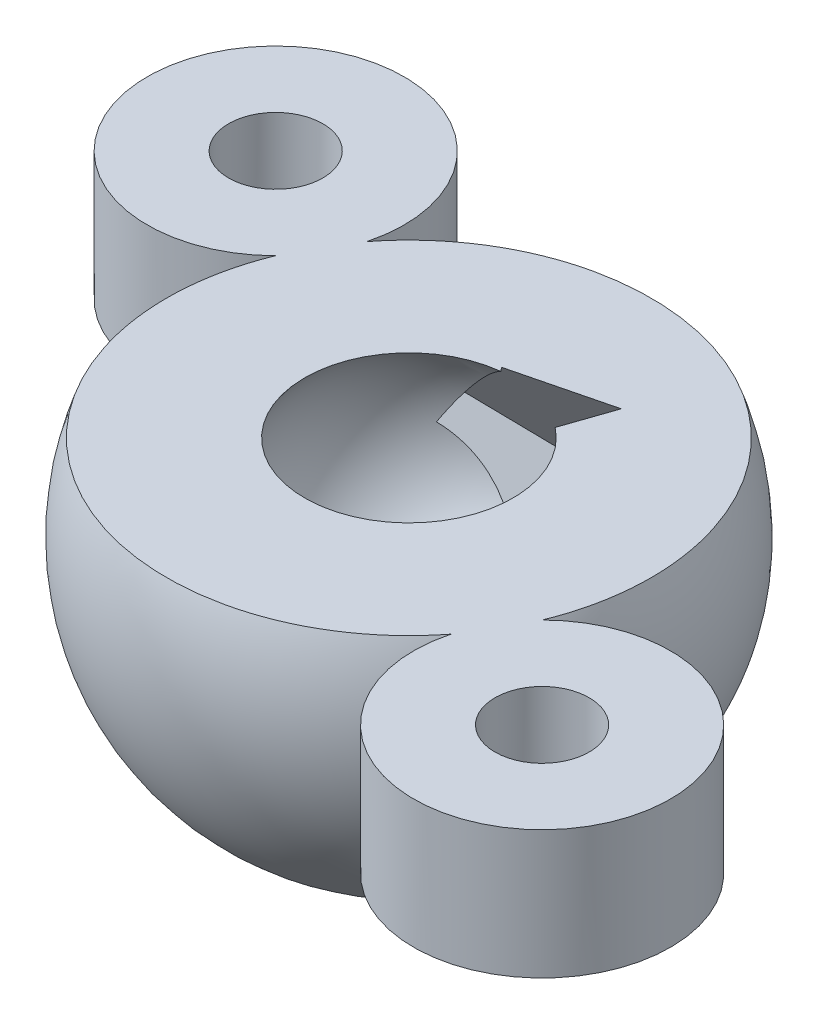
SolidWorks part; units mm, degrees
other "Compression Link 2 Fixed Ball Retainer"
ref_plane "Front Plane" through (0, 0, 0) normal (0, 0, 1) x (1, 0, 0)
ref_plane "Top Plane" through (0, 0, 0) normal (0, 1, 0) x (1, 0, 0)
ref_plane "Right Plane" through (0, 0, 0) normal (1, 0, 0) x (0, 0, -1)
sketch3d "Retainer Dome axis line"
  line L0 (-62.6314, -73, 30.9808) -> (-79.9519, -73, 20.9808) construction
ref_axis "Retainer Dome axis" through (-62.6314, -73, 30.9808) along (-0.866, 0, -0.5)
sketch3d "Retainer Dome Sketch datum points"
  point P0 (-71.2917, -73, 25.9808)
  point P1 (-76.2917, -73, 34.641)
  point P2 (-79.9519, -73, 20.9808)
ref_plane "Retainer Dome Sketch plane" through (0, -73, 0) normal (0, -1, 0) x (-1, 0, 0)
sketch "Retainer Dome Sketch" plane through (0, -73, 0) normal (0, -1, 0) x (-1, 0, 0)
  line L0 (76.4878, -22.9808) -> (66.0955, -28.9808)
  arc A0 (66.0955, -28.9808) -> (76.4878, -22.9808) centre (71.2917, -25.9808) ccw
revolve "Retainer Dome" add sketch "Retainer Dome Sketch" angle 360 about axis through (-62.6314, -73, 30.9808) along (-0.866, 0, -0.5)
sketch3d "Dome Trim Sketch datum points"
  point P0 (-61.7295, -71, 23.4186)
  point P1 (-66.7295, -71, 32.0788)
  point P2 (-61.7295, -61, 23.4186)
ref_plane "Dome Trim Sketch plane" through (-36.1566, 0, -20.875) normal (-0.866, 0, -0.5) x (-0.5, 0, 0.866)
sketch "Dome Trim Sketch" plane through (-36.1566, 0, -20.875) normal (-0.866, 0, -0.5) x (-0.5, 0, 0.866)
  line L0 (51.1458, -71) -> (65.1458, -71)
  line L1 (65.1458, -71) -> (65.1458, -66)
  line L2 (65.1458, -66) -> (51.1458, -66)
  line L3 (51.1458, -66) -> (51.1458, -71)
extrude "Dome Trim" cut sketch "Dome Trim Sketch" along normal blind 14
sketch3d "Retainer Feature 3 profile datum points"
  point P0 (-63.9304, -71, 30.2308)
  point P1 (-53.9304, -71, 30.2308)
  point P2 (-63.9304, -71, 40.2308)
ref_plane "Retainer Feature 3 profile plane" through (0, -71, 0) normal (0, -1, 0) x (-1, 0, 0)
sketch "Retainer Feature 3 profile" plane through (0, -71, 0) normal (0, -1, 0) x (-1, 0, 0)
  circle A0 centre (63.9304, -30.2308) radius 3
extrude "Retainer Feature 3" add sketch "Retainer Feature 3 profile" along normal blind 3
sketch3d "Retainer Feature 4 profile datum points"
  point P0 (-78.6529, -71, 21.7308)
  point P1 (-68.6529, -71, 21.7308)
  point P2 (-78.6529, -71, 31.7308)
ref_plane "Retainer Feature 4 profile plane" through (0, -71, 0) normal (0, -1, 0) x (-1, 0, 0)
sketch "Retainer Feature 4 profile" plane through (0, -71, 0) normal (0, -1, 0) x (-1, 0, 0)
  circle A0 centre (78.6529, -21.7308) radius 3
extrude "Retainer Feature 4" add sketch "Retainer Feature 4 profile" along normal blind 3
sketch3d "Spherical Seat axis line"
  line L0 (-62.6314, -73, 30.9808) -> (-79.9519, -73, 20.9808) construction
ref_axis "Spherical Seat axis" through (-62.6314, -73, 30.9808) along (-0.866, 0, -0.5)
sketch3d "Spherical Seat Sketch datum points"
  point P0 (-71.2917, -73, 25.9808)
  point P1 (-76.2917, -73, 34.641)
  point P2 (-79.9519, -73, 20.9808)
ref_plane "Spherical Seat Sketch plane" through (0, -73, 0) normal (0, -1, 0) x (-1, 0, 0)
sketch "Spherical Seat Sketch" plane through (0, -73, 0) normal (0, -1, 0) x (-1, 0, 0)
  line L0 (74.0196, -24.4058) -> (68.5637, -27.5558)
  arc A0 (68.5637, -27.5558) -> (74.0196, -24.4058) centre (71.2917, -25.9808) ccw
revolve "Spherical Seat" cut sketch "Spherical Seat Sketch" angle 360 about axis through (-62.6314, -73, 30.9808) along (-0.866, 0, -0.5)
sketch3d "Retainer Feature 6 profile datum points"
  point P0 (-63.9304, -70, 30.2308)
  point P1 (-53.9304, -70, 30.2308)
  point P2 (-63.9304, -70, 40.2308)
ref_plane "Retainer Feature 6 profile plane" through (0, -70, 0) normal (0, -1, 0) x (-1, 0, 0)
sketch "Retainer Feature 6 profile" plane through (0, -70, 0) normal (0, -1, 0) x (-1, 0, 0)
  circle A0 centre (63.9304, -30.2308) radius 1.1
extrude "Retainer Feature 6" cut sketch "Retainer Feature 6 profile" along normal blind 4.25
sketch3d "Retainer Feature 7 profile datum points"
  point P0 (-63.9304, -72.8, 30.2308)
  point P1 (-53.9304, -72.8, 30.2308)
  point P2 (-63.9304, -72.8, 40.2308)
ref_plane "Retainer Feature 7 profile plane" through (0, -72.8, 0) normal (0, -1, 0) x (-1, 0, 0)
sketch "Retainer Feature 7 profile" plane through (0, -72.8, 0) normal (0, -1, 0) x (-1, 0, 0)
  circle A0 centre (63.9304, -30.2308) radius 2.1
extrude "Retainer Feature 7" cut sketch "Retainer Feature 7 profile" along normal blind 1.45
sketch3d "Retainer Feature 8 profile datum points"
  point P0 (-78.6529, -70, 21.7308)
  point P1 (-68.6529, -70, 21.7308)
  point P2 (-78.6529, -70, 31.7308)
ref_plane "Retainer Feature 8 profile plane" through (0, -70, 0) normal (0, -1, 0) x (-1, 0, 0)
sketch "Retainer Feature 8 profile" plane through (0, -70, 0) normal (0, -1, 0) x (-1, 0, 0)
  circle A0 centre (78.6529, -21.7308) radius 1.1
extrude "Retainer Feature 8" cut sketch "Retainer Feature 8 profile" along normal blind 4.25
sketch3d "Retainer Feature 9 profile datum points"
  point P0 (-78.6529, -72.8, 21.7308)
  point P1 (-68.6529, -72.8, 21.7308)
  point P2 (-78.6529, -72.8, 31.7308)
ref_plane "Retainer Feature 9 profile plane" through (0, -72.8, 0) normal (0, -1, 0) x (-1, 0, 0)
sketch "Retainer Feature 9 profile" plane through (0, -72.8, 0) normal (0, -1, 0) x (-1, 0, 0)
  circle A0 centre (78.6529, -21.7308) radius 2.1
extrude "Retainer Feature 9" cut sketch "Retainer Feature 9 profile" along normal blind 1.45
sketch3d "Middle Right Fixed Compression Ball Retainer 1 Angular Clearance Sketch 21 datum points"
  point P0 (-71.2917, -73, 25.9808)
  point P1 (-69.2533, -78.3859, 34.1562)
  point P2 (-78.4932, -79.4818, 23.5061)
ref_plane "Middle Right Fixed Compression Ball Retainer 1 Angular Clearance Sketch 21 plane" through (-14.2547, 11.5703, 11.1766) normal (0.6632, -0.5383, -0.52) x (-0.4037, 0.3277, -0.8542)
sketch "Middle Right Fixed Compression Ball Retainer 1 Angular Clearance Sketch 21" plane through (-14.2547, 11.5703, 11.1766) normal (0.6632, -0.5383, -0.52) x (-0.4037, 0.3277, -0.8542)
  line L0 (-14.8193, -98.8621) -> (-20.9448, -100.7163)
  line L1 (-20.9448, -100.7163) -> (-19.8439, -104.3533)
  line L2 (-19.8439, -104.3533) -> (-13.7184, -102.4991)
  line L3 (-13.7184, -102.4991) -> (-14.8193, -98.8621)
extrude "Retainer Feature 12" cut sketch "Middle Right Fixed Compression Ball Retainer 1 Angular Clearance Sketch 21" along normal blind 10
